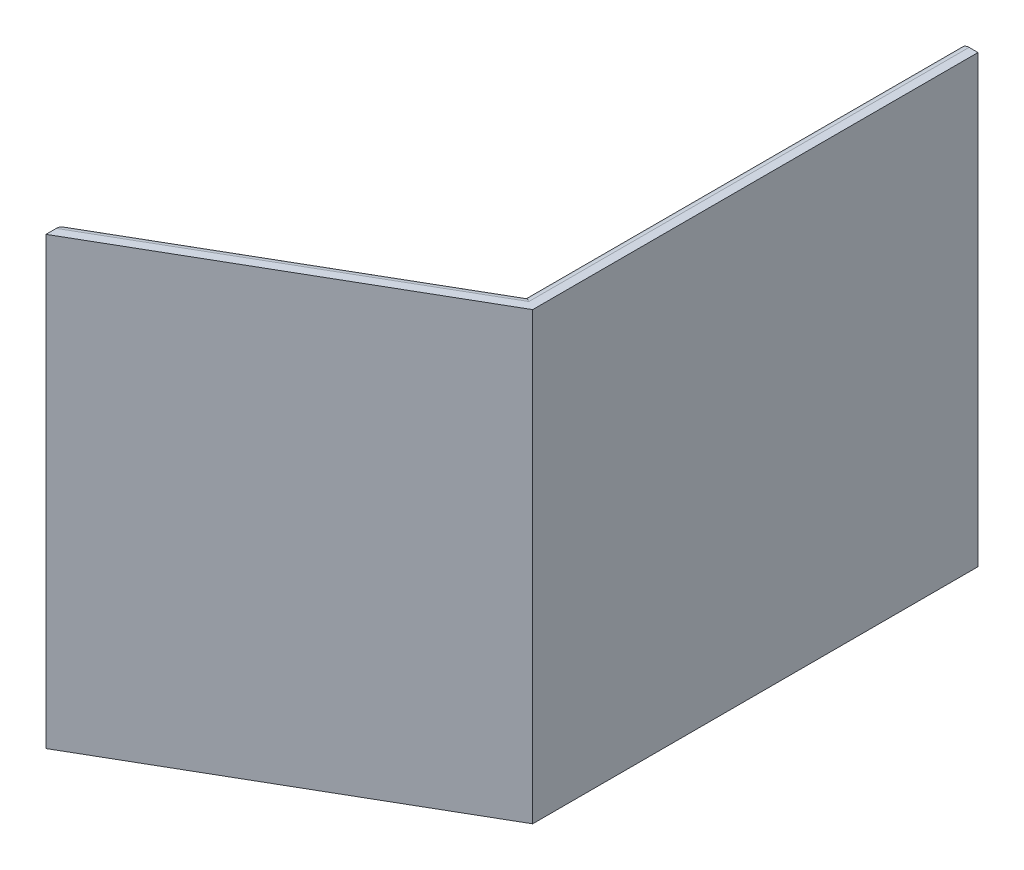
SolidWorks part; units mm, degrees
ref_plane "Front Plane" through (0, 0, 0) normal (0, 0, 1) x (1, 0, 0)
ref_plane "Top Plane" through (0, 0, 0) normal (0, 1, 0) x (1, 0, 0)
ref_plane "Right Plane" through (0, 0, 0) normal (1, 0, 0) x (0, 0, -1)
sketch "Sketch1" plane through (0, 0, 0) normal (0, 1, 0) x (1, 0, 0)
  line L0 (1026.3612, 29.8308) -> (1061.0023, 49.8308)
  line L1 (1061.0023, 49.8308) -> (1061.0023, 99.8308)
  line L2 (1061.0023, 99.8308) -> (1049.0023, 99.8308)
  line L3 (1049.0023, 99.8308) -> (1049.0023, 56.7591)
  line L4 (1049.0023, 56.7591) -> (1026.3612, 43.6873)
  line L5 (1026.3612, 43.6873) -> (1026.3612, 29.8308)
  dimension "D1" = 120
  dimension "D2" = 12
  dimension "D3" = 12
  dimension "D4" = 40
  dimension "D5" = 50
extrude "Boss-Extrude1" add sketch "Sketch1" along normal blind 50
sketch "Sketch2" plane through (0, 50, 0) normal (0, 1, 0) x (1, 0, 0)
  line L0 (1059.0023, 99.8308) -> (1059.0023, 50.9856)
  line L1 (1061.0023, 99.8308) -> (1049.0023, 99.8308) construction
  line L2 (1059.0023, 50.9856) -> (1026.3612, 32.1403)
  line L3 (1026.3612, 43.6873) -> (1026.3612, 29.8308) construction
  line L4 (1026.3612, 32.1403) -> (1013.24, 83.1623)
  line L5 (1013.24, 83.1623) -> (1049.0023, 102.2826)
  line L6 (1049.0023, 102.2826) -> (1059.0023, 99.8308)
  line L7 (1061.0023, 49.8308) -> (1061.0023, 99.8308) construction
  line L8 (1026.3612, 29.8308) -> (1061.0023, 49.8308) construction
  dimension "D1" = 2
  dimension "D2" = 2
other "AlignGroup1"
extrude "Cut-Extrude1" cut sketch "Sketch2" against normal blind 48
fillet "Fillet1" radius 1 4 edges at (1049.0023, 2, -78.295) (1037.6818, 2, -50.2232) (1042.6818, 50, -41.5629) (1059.0023, 50, -75.4082)
fillet "Fillet2" radius 2 2 edges at (1042.6818, 2, -41.5629) (1059.0023, 2, -75.4082)
sketch "Sketch3" plane through (0, 2, 0) normal (0, 1, 0) x (1, 0, 0)
  line L0 (1026.3612, 29.8308) -> (1061.0023, 49.8308) construction
  line L1 (1061.0023, 49.8308) -> (1061.0023, 99.8308) construction
  line L2 (1050.0023, 99.8308) -> (1057.0023, 99.8308) construction
  circle A0 centre (1039.9423, 46.3321) radius 1.6
  circle A1 centre (1053.5023, 59.8308) radius 1.6
  circle A2 centre (1053.5023, 89.8308) radius 1.6
  dimension "D1" = 3.2
  dimension "D2" = 3.2
  dimension "D3" = 3.2
  dimension "D4" = 7.5
  dimension "D5" = 7.5
  dimension "D6" = 7.5
  dimension "D7" = 10
  dimension "D8" = 10
  dimension "D9" = 21.06
extrude "Cut-Extrude2" cut sketch "Sketch3" against normal through all
